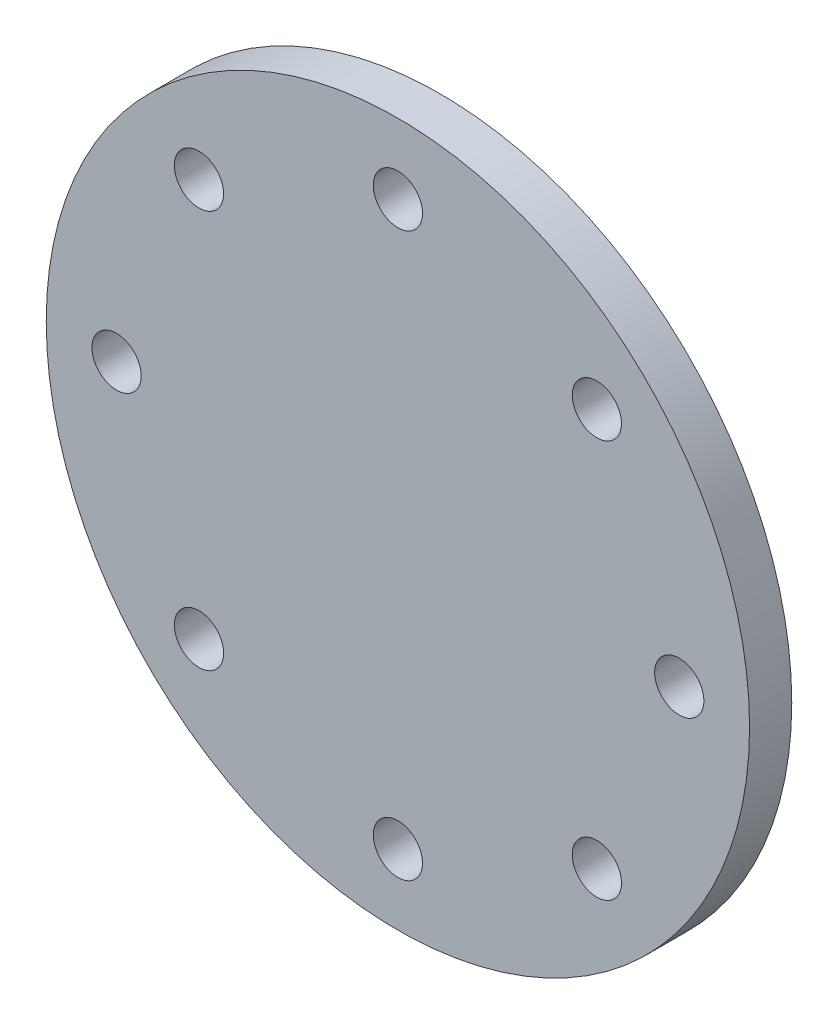
SolidWorks part; units mm, degrees
ref_plane "Front Plane" through (0, 0, 0) normal (0, 0, 1) x (1, 0, 0)
ref_plane "Top Plane" through (0, 0, 0) normal (0, 1, 0) x (1, 0, 0)
ref_plane "Right Plane" through (0, 0, 0) normal (1, 0, 0) x (0, 0, -1)
sketch "Sketch1" plane through (0, 0, 0) normal (0, 0, 1) x (1, 0, 0)
  circle A0 centre (0, 0) radius 25
  dimension "D1" = 50
extrude "Boss-Extrude1" add sketch "Sketch1" along normal blind 3
sketch "Sketch2" plane through (0, 0, 3) normal (0, 0, 1) x (1, 0, 0)
  line L0 (0, 20) -> (0, 0) construction
  circle A0 centre (0, 20) radius 1.75
  dimension "D2" = 3.5
  dimension "D1" = 20
extrude "Cut-Extrude1" cut sketch "Sketch2" against normal blind 3
pattern_circular "CirPattern1" count 8 over 360 about axis through (0, 0, 0) along (0, 0, 1) of "Cut-Extrude1"
